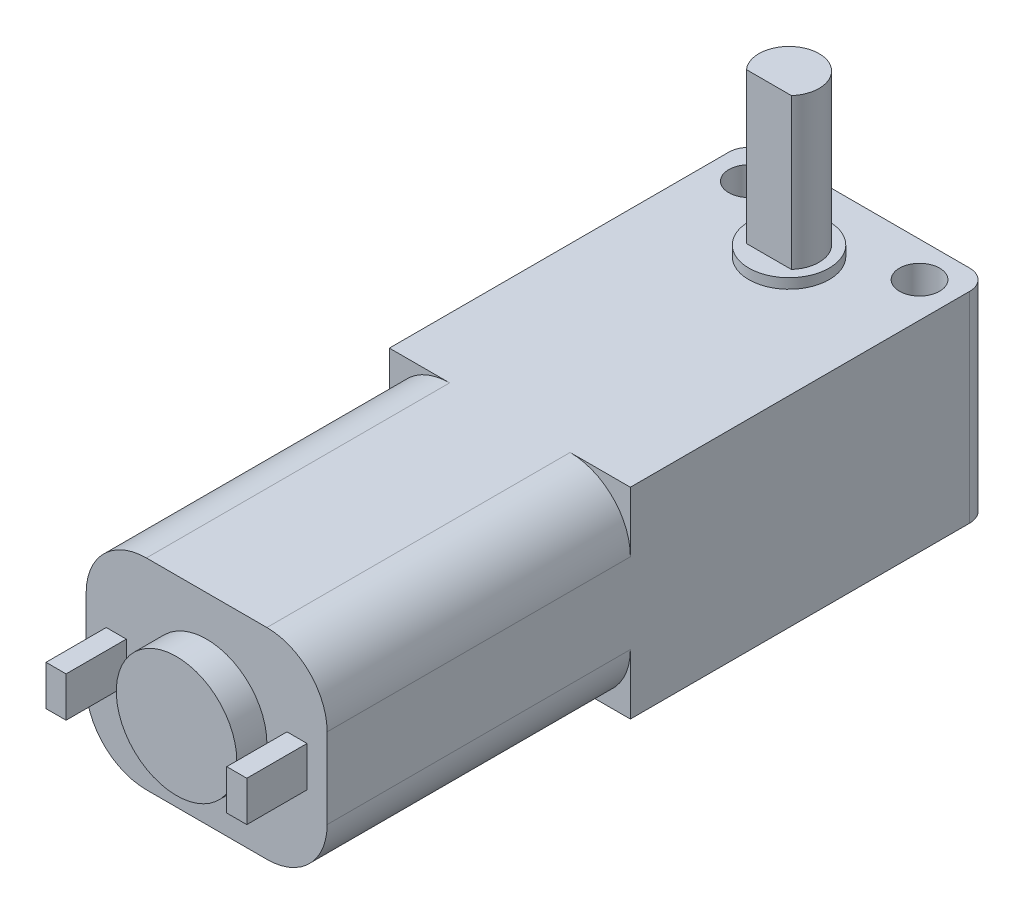
SolidWorks part; units mm, degrees
ref_plane "前视基准面" through (0, 0, 0) normal (0, 0, 1) x (1, 0, 0)
ref_plane "上视基准面" through (0, 0, 0) normal (0, 1, 0) x (1, 0, 0)
ref_plane "右视基准面" through (0, 0, 0) normal (1, 0, 0) x (0, 0, -1)
other "Configuration Table"
sketch "草图1" plane through (0, 0, 0) normal (0, 1, 0) x (1, 0, 0)
  line L1 (-6, 16.5) -> (6, 16.5)
  line L2 (-6, 16.5) -> (-6, -16.5)
  line L3 (-6, -16.5) -> (6, -16.5)
  line L4 (6, 16.5) -> (6, -16.5)
  point P4 (0, 16.5)
  point P5 (6, 0)
  dimension "D1" = 12
  dimension "D2" = 33
extrude "凸台-拉伸1" add sketch "草图1" along normal blind 10
sketch "草图3" plane through (0, 0, 16.5) normal (0, 0, 1) x (1, 0, 0)
  line L1 (-3, 10) -> (3, 10)
  line L2 (-6, 7) -> (-6, 3)
  line L3 (-3, 0) -> (3, 0)
  line L4 (6, 7) -> (6, 3)
  arc A0 (3, 0) -> (6, 3) centre (3, 3) ccw
  arc A1 (-6, 3) -> (-3, 0) centre (-3, 3) ccw
  arc A2 (3, 10) -> (6, 7) centre (3, 7) cw
  arc A3 (-3, 10) -> (-6, 7) centre (-3, 7) ccw
  point P8 (6, 0)
  point P15 (-6, 10)
  dimension "D1" = 3
extrude "切除-拉伸1" cut sketch "草图3" against normal blind 15.1 flip side to cut contours L2 A1 L3 A0 L4 A2 L1 A3
sketch "草图4" plane through (0, 0, 16.5) normal (0, 0, 1) x (1, 0, 0)
  line L0 (6, 7) -> (6, 3) construction
  circle A0 centre (0, 5) radius 3
  point P5 (6, 5)
  dimension "D1" = 6
extrude "凸台-拉伸2" add sketch "草图4" along normal blind 1.5
sketch "草图5" plane through (0, 0, 16.5) normal (0, 0, 1) x (1, 0, 0)
  line L0 (-6, 5) -> (6, 5) construction
  line L1 (-6, 7) -> (-6, 3) construction
  line L2 (6, 7) -> (6, 3) construction
  line L3 (0, 10) -> (0, 0) construction
  line L4 (-3, 10) -> (3, 10) construction
  line L5 (5, 4) -> (4, 4)
  line L6 (-5, 6) -> (-4, 6)
  line L7 (-5, 6) -> (-5, 4)
  line L8 (-5, 4) -> (-4, 4)
  line L9 (-4, 6) -> (-4, 4)
  line L10 (4, 6) -> (4, 4)
  line L11 (5, 6) -> (4, 6)
  line L12 (5, 6) -> (5, 4)
  point P15 (-5, 5)
  dimension "D1" = 1
  dimension "D2" = 1
  dimension "D3" = 2
extrude "凸台-拉伸3" add sketch "草图5" along normal blind 3
sketch "草图6" plane through (0, 10, 0) normal (0, 1, 0) x (1, 0, 0)
  line L0 (0, 16.5) -> (0, 6.5891) construction
  line L1 (6, 16.5) -> (-6, 16.5) construction
  circle A0 centre (0, 12.5) radius 2
  dimension "D1" = 4
  dimension "D2" = 4
extrude "凸台-拉伸4" add sketch "草图6" along normal blind 0.5
sketch "草图7" plane through (0, 10.5, 0) normal (0, 1, 0) x (1, 0, 0)
  circle A0 centre (0, 12.5) radius 1.5
  dimension "D1" = 3
extrude "凸台-拉伸5" add sketch "草图7" along normal blind 7.5
sketch "草图8" plane through (0, 18, 0) normal (0, 1, 0) x (1, 0, 0)
  line L0 (0, 14) -> (3.338, 14) construction
  line L1 (-2.5322, 11.5) -> (3.338, 11.5)
  line L2 (-2.5322, 11.5) -> (-2.5322, 8.7796)
  line L3 (-2.5322, 8.7796) -> (3.338, 8.7796)
  line L4 (3.338, 11.5) -> (3.338, 8.7796)
  circle A0 centre (0, 12.5) radius 1.5 construction
  circle A1 centre (0, 12.5) radius 1.5 construction
  dimension "D1" = 2.5
extrude "切除-拉伸2" cut sketch "草图8" against normal up to surface (7.5 mm away) up to face at (0, 10.5, -11)
fillet "圆角1" radius 1 2 edges at (6, 5, -16.5) (-6, 5, -16.5)
sketch "草图9" plane through (0, 10, 0) normal (0, 1, 0) x (1, 0, 0)
  line L0 (-4.25, 14.75) -> (4.25, 14.75) construction
  line L1 (5, 16.5) -> (-5, 16.5) construction
  line L2 (0, 12.5) -> (-3.8644, 12.5) construction
  circle A0 centre (-4.25, 14.75) radius 1
  circle A1 centre (4.25, 14.75) radius 1
  point P4 (0, 14.75)
  point P7 (0, 16.5)
  dimension "D1" = 2.25
  dimension "D3" = 2
  dimension "D2" = 8.5
extrude "切除-拉伸3" cut sketch "草图9" against normal through all
